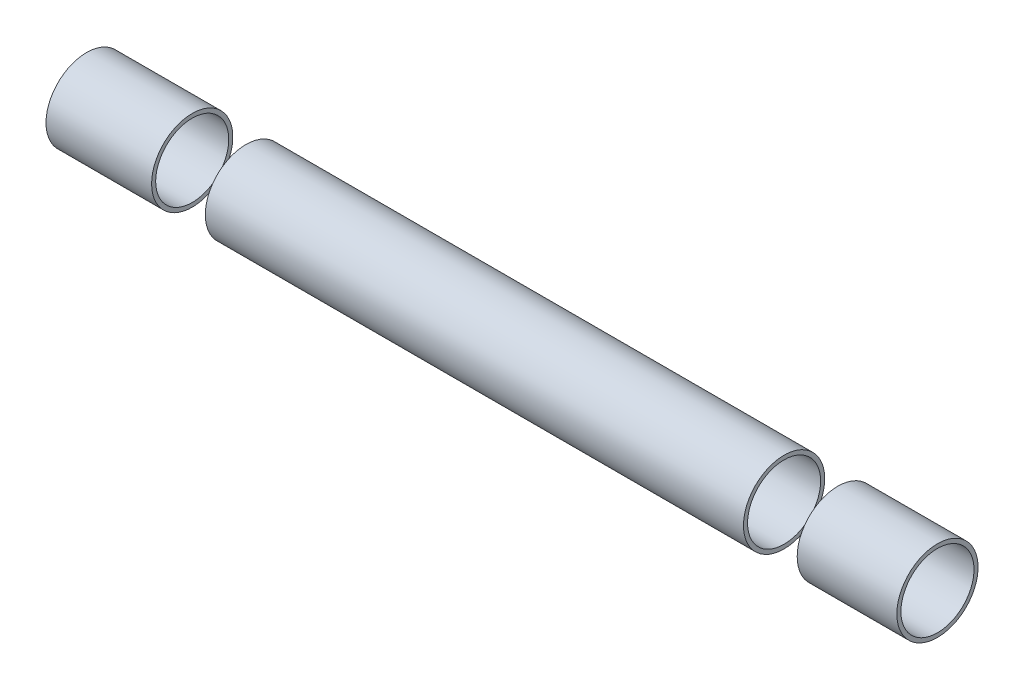
SolidWorks part; units mm, degrees
material "PC High Viscosity"
ref_plane "Front Plane" through (0, 0, 0) normal (0, 0, 1) x (1, 0, 0)
ref_plane "Top Plane" through (0, 0, 0) normal (0, 1, 0) x (1, 0, 0)
ref_plane "Right Plane" through (0, 0, 0) normal (1, 0, 0) x (0, 0, -1)
sketch "Sketch1" plane through (0, 0, 0) normal (1, 0, 0) x (0, 0, -1)
  circle A0 centre (0, 0) radius 15.875
  dimension "D1" = 31.75
extrude "Extrude-Thin1" add sketch "Sketch1" along normal mid plane 334.899 thin thin type one direction reverse wall 1.5875
sketch "Sketch2" plane through (0, 0, 0) normal (0, 0, 1) x (1, 0, 0)
  line L0 (-167.4495, -15.875) -> (167.4495, -15.875) construction
  line L1 (105.1745, -15.875) -> (126.1745, -15.875)
  line L2 (105.1745, -15.875) -> (105.1745, 15.875)
  line L3 (105.1745, 15.875) -> (126.1745, 15.875)
  line L4 (126.1745, -15.875) -> (126.1745, 15.875)
  line L5 (167.4495, 15.875) -> (-167.4495, 15.875) construction
  line L6 (167.4495, -15.875) -> (167.4495, 15.875) construction
  line L7 (0, 0) -> (0, 11.1276) construction
  line L8 (-126.1745, -15.875) -> (-126.1745, 15.875)
  line L9 (-105.1745, 15.875) -> (-126.1745, 15.875)
  line L10 (-105.1745, -15.875) -> (-105.1745, 15.875)
  line L11 (-105.1745, -15.875) -> (-126.1745, -15.875)
  line L13 (167.4495, -15.875) -> (165.1254, -15.875)
  line L14 (167.4495, -15.875) -> (167.4495, 15.875)
  line L15 (167.4495, 15.875) -> (165.1254, 15.875)
  line L16 (165.1254, -15.875) -> (165.1254, 15.875)
  dimension "D1" = 41.275
  dimension "D2" = 21
  dimension "D3" = 2.3241
extrude "Cut-Extrude1" cut sketch "Sketch2" against normal through all both and the other way through all
other "Save Bodies1"
equation "\"D2@Sketch2\"=21mm"
